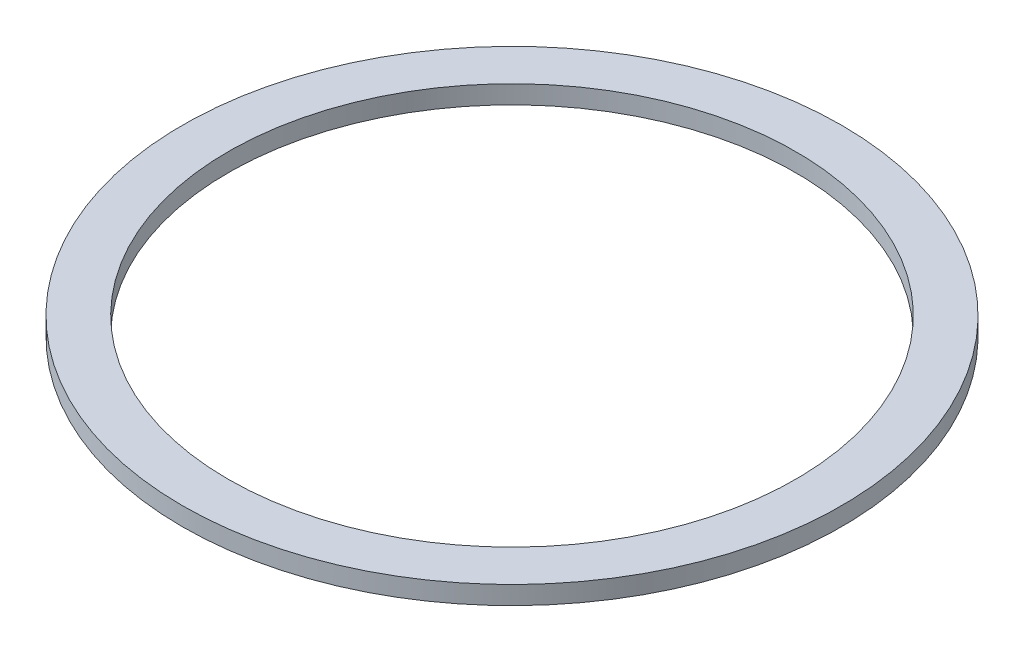
SolidWorks part; units mm, degrees
ref_plane "Plan de face" through (0, 0, 0) normal (0, 0, 1) x (1, 0, 0)
ref_plane "Plan de dessus" through (0, 0, 0) normal (0, 1, 0) x (1, 0, 0)
ref_plane "Plan de droite" through (0, 0, 0) normal (1, 0, 0) x (0, 0, -1)
sketch "Esquisse1" plane through (0, 0, 0) normal (0, 1, 0) x (1, 0, 0)
  circle A0 centre (0, 0) radius 18
  circle A1 centre (0, 0) radius 15.5
  dimension "D1" = 36
  dimension "D2" = 31
extrude "Boss.-Extru.1" add sketch "Esquisse1" along normal blind 1
